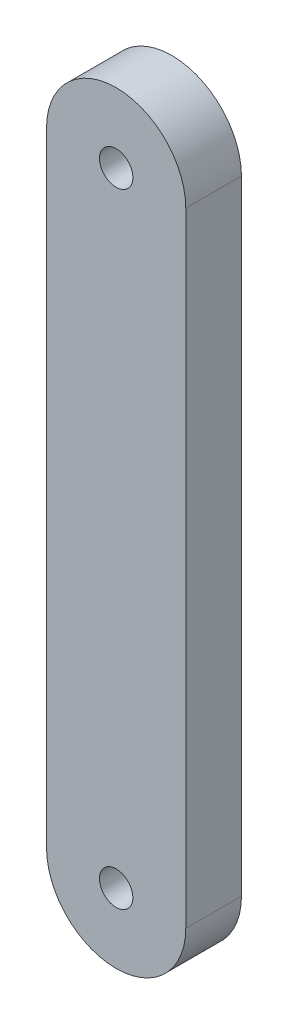
SolidWorks part; units mm, degrees
ref_plane "Front Plane" through (0, 0, 0) normal (0, 0, 1) x (1, 0, 0)
ref_plane "Top Plane" through (0, 0, 0) normal (0, 1, 0) x (1, 0, 0)
ref_plane "Right Plane" through (0, 0, 0) normal (1, 0, 0) x (0, 0, -1)
sketch "Sketch1" plane through (0, 0, 0) normal (0, 0, 1) x (1, 0, 0)
  line L0 (-12.5, 0) -> (-12.5, -112)
  line L1 (12.5, 0) -> (12.5, -112)
  line L2 (-12.5, -56) -> (12.5, -56) construction
  circle A0 centre (0, 0) radius 3
  arc A1 (12.5, 0) -> (-12.5, 0) centre (0, 0) ccw
  arc A2 (12.5, -112) -> (-12.5, -112) centre (0, -112) cw
  circle A3 centre (0, -112) radius 3
  dimension "D1" = 6
  dimension "D2" = 25
  dimension "D3" = 112
extrude "Boss-Extrude1" add sketch "Sketch1" along normal blind 10
